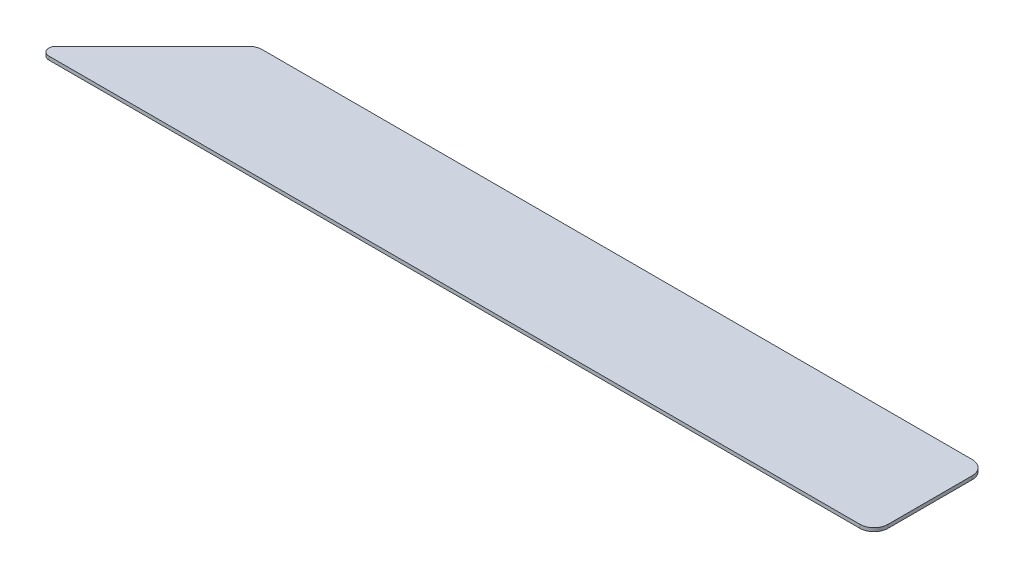
SolidWorks part; units mm, degrees
ref_plane "Front Plane" through (0, 0, 0) normal (0, 0, 1) x (1, 0, 0)
ref_plane "Top Plane" through (0, 0, 0) normal (0, 1, 0) x (1, 0, 0)
ref_plane "Right Plane" through (0, 0, 0) normal (1, 0, 0) x (0, 0, -1)
sketch "Sketch1" plane through (0, 0, 0) normal (0, 1, 0) x (1, 0, 0)
  line L0 (7.6651, 0) -> (374.65, 0)
  line L1 (381, 6.35) -> (381, 44.45)
  line L2 (374.65, 50.8) -> (53.4303, 50.8)
  line L3 (48.9401, 48.9401) -> (5.4201, 5.4201)
  arc A0 (381, 44.45) -> (374.65, 50.8) centre (374.65, 44.45) ccw
  arc A1 (381, 6.35) -> (374.65, 0) centre (374.65, 6.35) cw
  arc A2 (53.4303, 50.8) -> (48.9401, 48.9401) centre (53.4303, 44.45) ccw
  arc A3 (7.6651, 0) -> (5.4201, 5.4201) centre (7.6651, 3.175) cw
  point P7 (381, 50.8)
  point P10 (381, 0)
  point P13 (50.8, 50.8)
  point P16 (0, 0)
  dimension "D4" = 6.35
  dimension "D5" = 6.35
  dimension "D6" = 6.35
  dimension "D7" = 3.175
  dimension "D1" = 50.8
  dimension "D2" = 381
  dimension "D3" = 330.2
extrude "Boss-Extrude1" add sketch "Sketch1" along normal blind 1.5875
